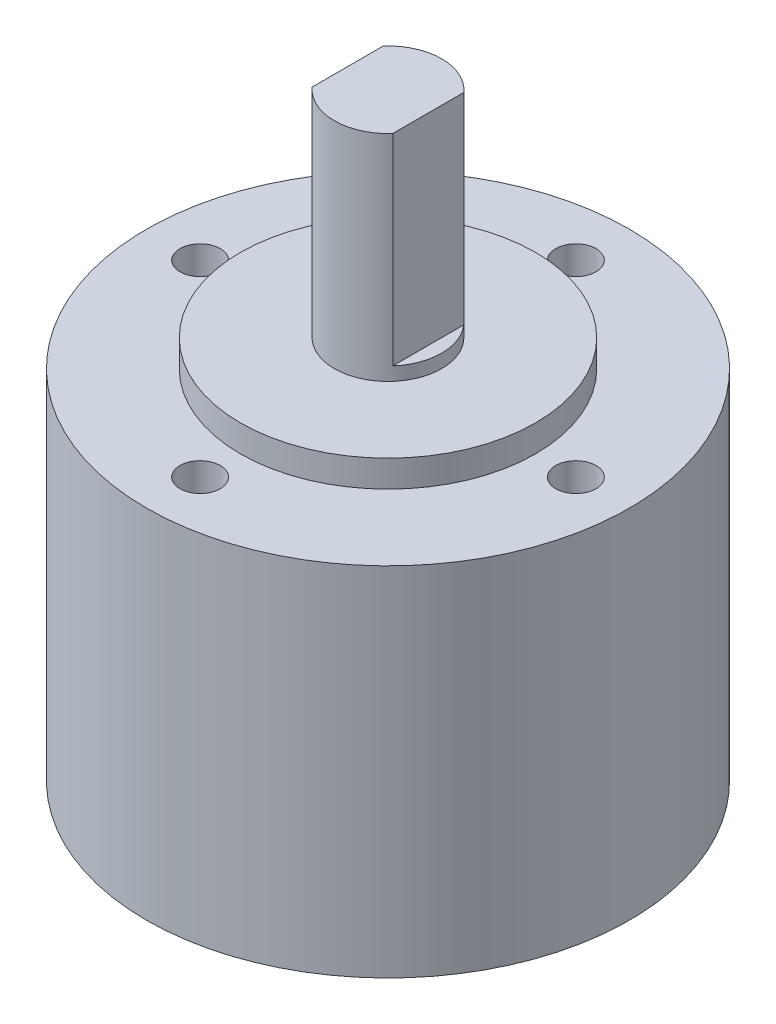
SolidWorks part; units mm, degrees
ref_plane "Front Plane" through (0, 0, 0) normal (0, 0, 1) x (1, 0, 0)
ref_plane "Top Plane" through (0, 0, 0) normal (0, 1, 0) x (1, 0, 0)
ref_plane "Right Plane" through (0, 0, 0) normal (1, 0, 0) x (0, 0, -1)
sketch "Sketch1" plane through (0, 0, 0) normal (0, 1, 0) x (1, 0, 0)
  circle A0 centre (0, 0) radius 18
  dimension "D1" = 36
extrude "Boss-Extrude1" add sketch "Sketch1" along normal mid plane 26.6
sketch "Sketch2" plane through (0, 13.3, 0) normal (0, 1, 0) x (1, 0, 0)
  circle A0 centre (0, 0) radius 11
  dimension "D1" = 22
extrude "Boss-Extrude2" add sketch "Sketch2" along normal blind 2
sketch "Sketch4" plane through (0, 15.3, 0) normal (0, 1, 0) x (1, 0, 0)
  circle A0 centre (0, 0) radius 14 construction
  circle A1 centre (-14, 0) radius 1.5
  circle A2 centre (0, -14) radius 1.5
  circle A3 centre (14, 0) radius 1.5
  circle A4 centre (0, 14) radius 1.5
  dimension "D1" = 28
  dimension "D2" = 3
extrude "Cut-Extrude1" cut sketch "Sketch4" against normal through all
sketch "Sketch5" plane through (0, 15.3, 0) normal (0, 1, 0) x (1, 0, 0)
  circle A0 centre (0, 0) radius 4
  dimension "D1" = 8
extrude "Boss-Extrude3" add sketch "Sketch5" along normal blind 16
sketch "Sketch6" plane through (0, 31.3, 0) normal (0, 1, 0) x (1, 0, 0)
  line L0 (-3, -4) -> (-3, 4)
  line L1 (3, -4) -> (3, 4)
  arc A1 (-3, 4) -> (-3, -4) centre (0, 0) ccw
  arc A2 (3, -4) -> (3, 4) centre (0, 0) ccw
  dimension "D2" = 5
  dimension "D1" = 6
extrude "Cut-Extrude2" cut sketch "Sketch6" against normal offset from surface (15 mm away) 1 up to face at (0, 15.3, 4)
